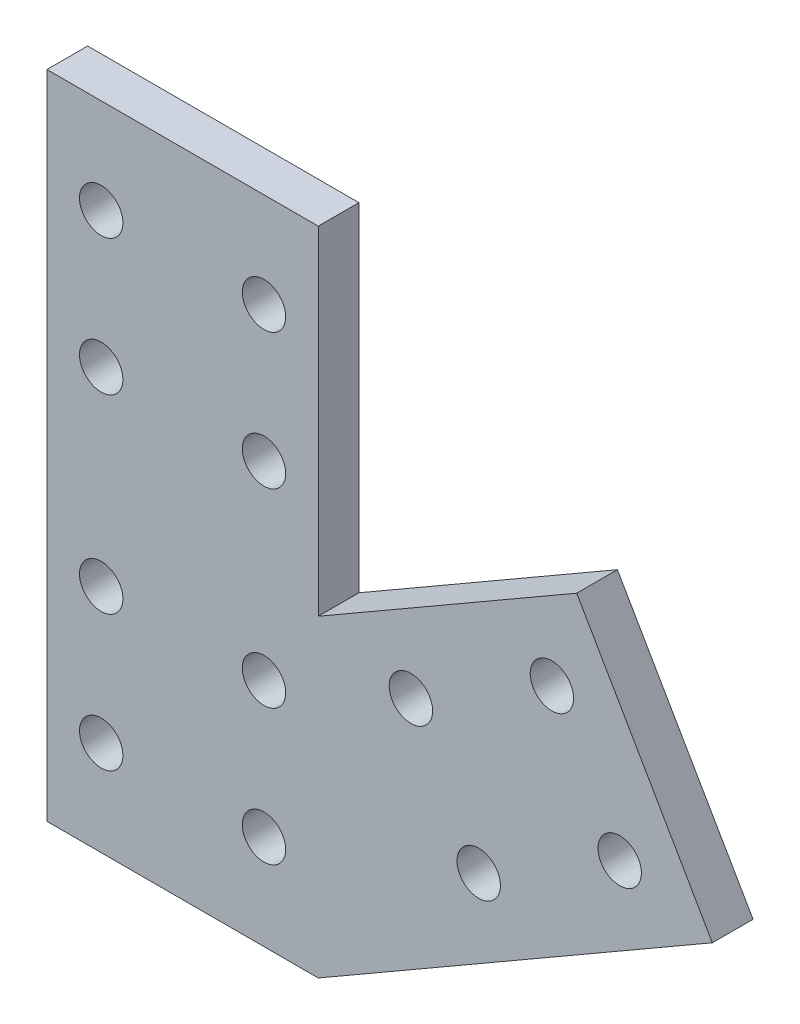
SolidWorks part; units mm, degrees
material "Thornel VCB-20 碳布"
ref_plane "前视基准面" through (0, 0, 0) normal (0, 0, 1) x (1, 0, 0)
ref_plane "上视基准面" through (0, 0, 0) normal (0, 1, 0) x (1, 0, 0)
ref_plane "右视基准面" through (0, 0, 0) normal (1, 0, 0) x (0, 0, -1)
other "Configuration Table"
sketch "草图1" plane through (0, 0, 0) normal (0, 0, 1) x (1, 0, 0)
  line L0 (0, 48) -> (0, 0)
  line L1 (0, 48) -> (20, 48)
  line L2 (20, 48) -> (20, 23.094)
  line L3 (20, 23.094) -> (39.0526, 34.094)
  line L4 (39.0526, 34.094) -> (49.0526, 16.7735)
  line L5 (49.0526, 16.7735) -> (20, 0)
  line L7 (20, 0) -> (0, 0)
  line L8 (20, 23.094) -> (20, 0) construction
  dimension "D1" = 60
  dimension "D2" = 20
  dimension "D3" = 20
  dimension "D4" = 48
  dimension "D5" = 22
extrude "凸台-拉伸1" add sketch "草图1" along normal blind 3
sketch "草图2" plane through (0, 0, 0) normal (0, 0, -1) x (-1, 0, 0)
  line L0 (-42.2224, 18.6036) -> (-21.4378, 6.6036) construction
  line L1 (-21.4378, 6.6036) -> (-16.4378, 15.2639) construction
  line L2 (-16.4378, 15.2639) -> (-37.2224, 27.2639) construction
  line L3 (-37.2224, 27.2639) -> (-42.2224, 18.6036) construction
  line L4 (-20, 0) -> (-49.0526, 16.7735) construction
  line L5 (-49.0526, 16.7735) -> (-39.0526, 34.094) construction
  line L6 (-39.0526, 34.094) -> (-20, 23.094) construction
  line L7 (0, 48) -> (0, 0) construction
  line L8 (-16, 7) -> (-4, 7) construction
  line L9 (-16, 7) -> (-16, 41) construction
  line L10 (-16, 41) -> (-4, 41) construction
  line L11 (-4, 7) -> (-4, 41) construction
  line L12 (-20, 48) -> (0, 48) construction
  circle A0 centre (-42.2224, 18.6036) radius 1.6
  circle A1 centre (-37.2224, 27.2639) radius 1.6
  circle A2 centre (-26.8301, 21.2639) radius 1.6
  circle A3 centre (-31.8301, 12.6036) radius 1.6
  circle A4 centre (-21.4378, 6.6036) radius 1.6 construction
  circle A5 centre (-16.4378, 15.2639) radius 1.6 construction
  circle A6 centre (-16, 7) radius 1.6
  circle A7 centre (-16, 17) radius 1.6
  circle A8 centre (-4, 7) radius 1.6
  circle A9 centre (-4, 17) radius 1.6
  circle A10 centre (-16, 31) radius 1.6
  circle A11 centre (-16, 41) radius 1.6
  circle A12 centre (-4, 31) radius 1.6
  circle A13 centre (-4, 41) radius 1.6
  dimension "D5" = 3.2
  dimension "D10" = 3.2
  dimension "D1" = 10
  dimension "D2" = 5
  dimension "D3" = 24
  dimension "D4" = 5
  dimension "D6" = 34
  dimension "D7" = 12
  dimension "D8" = 4
  dimension "D9" = 7
  dimension "D11" = 10
  dimension "D12" = 10
  dimension "D13" = 10
  dimension "D14" = 10
extrude "切除-拉伸1" cut sketch "草图2" against normal blind 3
